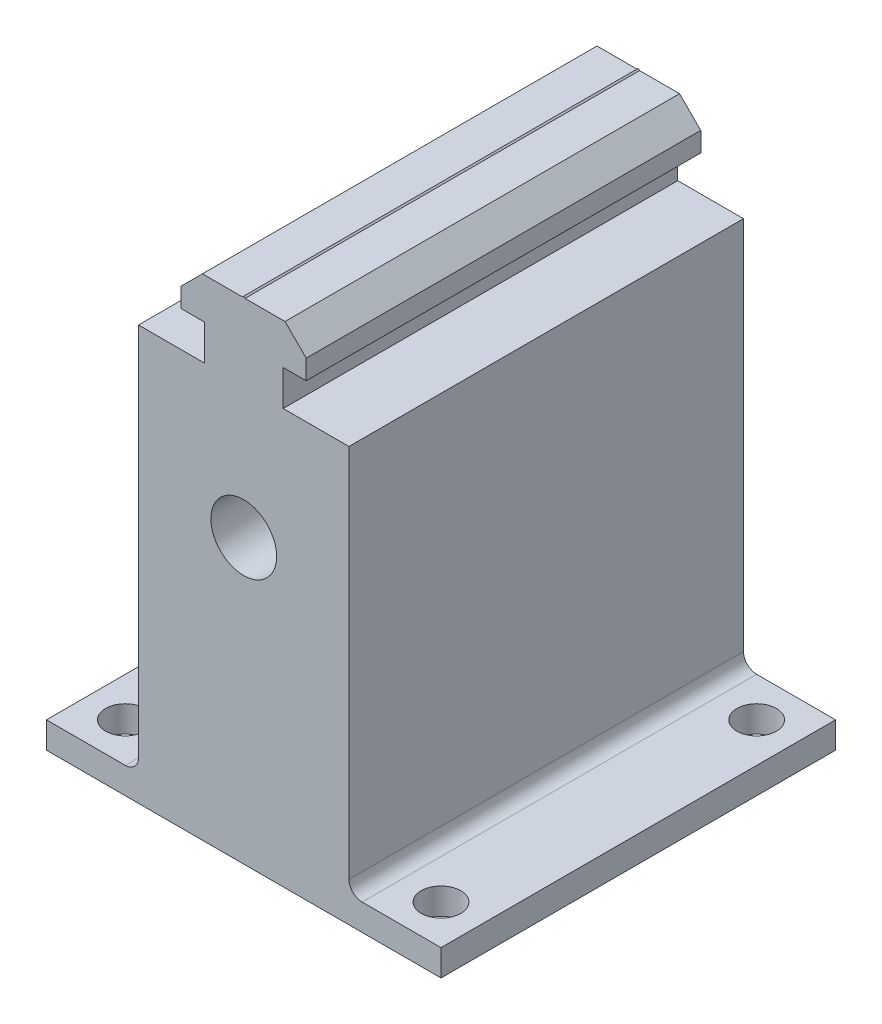
SolidWorks part; units mm, degrees
ref_plane "Front Plane" through (0, 0, 0) normal (0, 0, 1) x (1, 0, 0)
ref_plane "Top Plane" through (0, 0, 0) normal (0, 1, 0) x (1, 0, 0)
ref_plane "Right Plane" through (0, 0, 0) normal (1, 0, 0) x (0, 0, -1)
sketch "Sketch1" plane through (0, 0, 0) normal (0, 1, 0) x (1, 0, 0)
  line L0 (0, 15) -> (0, -15) construction
  line L1 (-15, -15) -> (15, -15)
  line L2 (-15, -15) -> (-15, 15)
  line L3 (-15, 15) -> (15, 15)
  line L4 (15, -15) -> (15, 15)
  line L5 (-15, -15) -> (15, 15) construction
  line L6 (-15, 15) -> (15, -15) construction
  line L7 (-15, 0) -> (15, 0) construction
  circle A0 centre (-12, 12) radius 1.5
  circle A1 centre (12, 12) radius 1.5
  circle A2 centre (12, -12) radius 1.5
  circle A3 centre (-12, -12) radius 1.5
  arc A4 (-15, 7) -> (-7, 15) centre (-15, 15) ccw
  arc A5 (15, 7) -> (7, 15) centre (15, 15) cw
  arc A6 (15, -7) -> (7, -15) centre (15, -15) ccw
  arc A7 (-15, -7) -> (-7, -15) centre (-15, -15) cw
  point P0 (0, 0)
  dimension "D2" = 3
  dimension "D4" = 16
  dimension "D1" = 30
  dimension "D3" = 3
extrude "Boss-Extrude1" add sketch "Sketch1" along normal blind 2 contours A7 L2 L1 A3 | L4 A6 L1 A2 | L2 A7 L1 A6 L4 A5 L3 A4 | A5 L4 L3 A1 | L2 A4 L3 A0
sketch "Sketch10" plane through (0, 2, 0) normal (0, 1, 0) x (1, 0, 0)
  line L0 (-15, 15) -> (15, 15) construction
  line L1 (-8, 15) -> (8, 15)
  line L2 (-8, 15) -> (-8, -15)
  line L3 (-8, -15) -> (8, -15)
  line L4 (8, 15) -> (8, -15)
  line L5 (-15, -15) -> (15, -15) construction
  point P8 (0, 15)
  dimension "D1" = 16
extrude "Boss-Extrude2" add sketch "Sketch10" along normal blind 29.5
fillet "Fillet1" radius 1 2 edges at (8, 2, 0) (-8, 2, 0)
sketch "Sketch11" plane through (0, 0, 15) normal (0, 0, 1) x (1, 0, 0)
  line L0 (-8, 31.5) -> (8, 31.5) construction
  circle A0 centre (0, 21.5) radius 2.5
  dimension "D1" = 5
  dimension "D2" = 10
extrude "Cut-Extrude1" cut sketch "Sketch11" against normal blind 32.5
sketch "Sketch13" plane through (0, 0, 15) normal (0, 0, 1) x (1, 0, 0)
  line L0 (-3, 34.2) -> (-3, 28.8)
  line L2 (3, 34.2) -> (3, 28.8)
  line L3 (3, 28.8) -> (4.75, 28.8)
  line L5 (-3, 28.8) -> (-4.75, 28.8)
  line L6 (3, 34.2) -> (4.75, 34.2)
  line L7 (-3, 34.2) -> (-4.75, 34.2)
  line L9 (-15, 0) -> (15, 0)
  line L10 (15, 0) -> (15, 2)
  line L11 (15, 2) -> (9, 2)
  line L12 (8, 3) -> (8, 31.5)
  line L13 (8, 31.5) -> (-8, 31.5)
  line L14 (-8, 31.5) -> (-8, 3)
  line L15 (-9, 2) -> (-15, 2)
  line L16 (-15, 2) -> (-15, 0)
  line L17 (-15, 0) -> (15, 0)
  line L18 (15, 0) -> (15, 2)
  line L19 (15, 2) -> (9, 2)
  line L20 (8, 3) -> (8, 31.5)
  line L21 (8, 31.5) -> (-8, 31.5)
  line L22 (-8, 31.5) -> (-8, 3)
  line L23 (-9, 2) -> (-15, 2)
  line L24 (-15, 2) -> (-15, 0)
  arc A2 (8, 3) -> (9, 2) centre (9, 3) ccw
  arc A3 (-9, 2) -> (-8, 3) centre (-9, 3) ccw
  arc A4 (8, 3) -> (9, 2) centre (9, 3) ccw
  arc A5 (-9, 2) -> (-8, 3) centre (-9, 3) ccw
  point P18 (3, 31.5)
  point P20 (0, 31.5)
  point P21 (-3, 31.5)
  line B0 (0, 41.5) -> (0, 31.5) construction
  line B1 (0, 37.4) -> (0.1, 37.3)
  line B2 (0.1, 37.3) -> (3.1393, 37.3)
  line B3 (3.1393, 37.3) -> (4.75, 35.6893)
  line B4 (4.75, 35.6893) -> (4.75, 33.3)
  line B5 (4.75, 33.3) -> (3, 33.3)
  line B6 (3, 33.3) -> (3, 33.25)
  line B7 (3, 33.25) -> (4.75, 31.5)
  line B8 (4.75, 31.5) -> (-4.75, 31.5)
  line B9 (0, 41.5) -> (5.9927, 35.5073) construction
  line B10 (-3, 33.25) -> (-4.75, 31.5)
  line B11 (-3, 33.3) -> (-3, 33.25)
  line B12 (-4.75, 33.3) -> (-3, 33.3)
  line B13 (-4.75, 35.6893) -> (-4.75, 33.3)
  line B14 (-3.1393, 37.3) -> (-4.75, 35.6893)
  line B15 (-0.1, 37.3) -> (-3.1393, 37.3)
  line B16 (0, 37.4) -> (-0.1, 37.3)
  line M9 (8, 31.5) -> (-8, 31.5)
  dimension "D1" = 0
sketch_block_instance "V Slot 1-11"
sketch_block "V Slot 1" parameters "D1"=10, "D2"=9.5, "D3"=4, "D4"=1.8, "D5"=0.1, "D6"=45, "D7"=9.5, "D8"=1.5, "D9"=6, "D10"=2.6393
extrude "Boss-Extrude4" add sketch "Sketch13" against normal blind 30 contours B1 B16 B15 B14 B13 L7 L0 L2 L6 B4 B3 B2 M9
